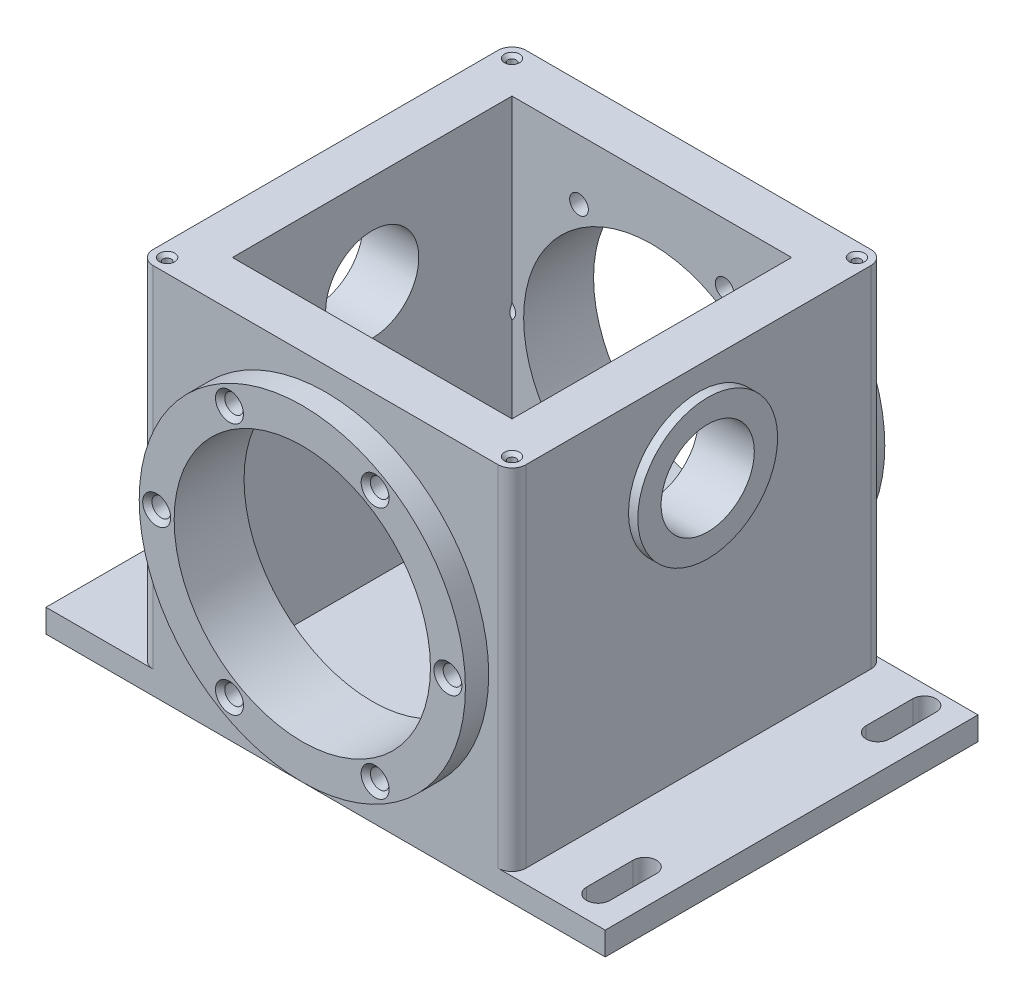
SolidWorks part; units mm, degrees
ref_plane "Front Plane" through (0, 0, 0) normal (0, 0, 1) x (1, 0, 0)
ref_plane "Top Plane" through (0, 0, 0) normal (0, 1, 0) x (1, 0, 0)
ref_plane "Right Plane" through (0, 0, 0) normal (1, 0, 0) x (0, 0, -1)
sketch "Sketch4" plane through (0, 0, 0) normal (0, 1, 0) x (1, 0, 0)
  line L1 (-76.2, -50.8) -> (76.2, -50.8)
  line L2 (-76.2, -50.8) -> (-76.2, 50.8)
  line L3 (-76.2, 50.8) -> (76.2, 50.8)
  line L4 (76.2, -50.8) -> (76.2, 50.8)
  line L5 (-76.2, -50.8) -> (76.2, 50.8) construction
  line L6 (-76.2, 50.8) -> (76.2, -50.8) construction
  point P0 (0, 0)
  dimension "D1" = 152.4
  dimension "D2" = 101.6
extrude "Boss-Extrude3" add sketch "Sketch4" along normal blind 6.35
sketch "Sketch5" plane through (0, 6.35, 0) normal (0, 1, 0) x (1, 0, 0)
  line L0 (76.2, 50.8) -> (-76.2, 50.8) construction
  line L1 (-50.8, -50.8) -> (50.8, -50.8)
  line L2 (-50.8, -50.8) -> (-50.8, 50.8)
  line L3 (-50.8, 50.8) -> (50.8, 50.8)
  line L4 (50.8, -50.8) -> (50.8, 50.8)
  line L5 (-50.8, -50.8) -> (50.8, 50.8) construction
  line L6 (-50.8, 50.8) -> (50.8, -50.8) construction
  point P0 (0, 0)
  dimension "D1" = 101.6
extrude "Boss-Extrude4" add sketch "Sketch5" along normal blind 95.25
sketch "Sketch6" plane through (0, 101.6, 0) normal (0, 1, 0) x (1, 0, 0)
  line L5 (50.8, 50.8) -> (-50.8, 50.8) construction
  line L6 (-38.1, -38.1) -> (38.1, -38.1)
  line L10 (-38.1, -38.1) -> (-38.1, 38.1)
  line L11 (-38.1, 38.1) -> (38.1, 38.1)
  line L12 (38.1, -38.1) -> (38.1, 38.1)
  line L13 (-38.1, -38.1) -> (38.1, 38.1) construction
  line L14 (-38.1, 38.1) -> (38.1, -38.1) construction
  line L15 (50.8, -50.8) -> (50.8, 50.8) construction
  point P0 (0, 0)
  dimension "D1" = 12.7
  dimension "D2" = 12.7
extrude "Cut-Extrude1" cut sketch "Sketch6" against normal blind 95.25
sketch "Sketch7" plane through (0, 0, 50.8) normal (0, 0, 1) x (1, 0, 0)
  line L0 (-50.8, 101.6) -> (50.8, 101.6) construction
  circle A0 centre (0, 50.8) radius 44.45
  dimension "D1" = 88.9
  dimension "D2" = 50.8
extrude "Boss-Extrude5" add sketch "Sketch7" along normal blind 6.35
mirror "Mirror2" about plane through (0, 0, 0) normal (0, 0, 1) of "Boss-Extrude5"
sketch "Sketch8" plane through (0, 0, 57.15) normal (0, 0, 1) x (1, 0, 0)
  circle A0 centre (0, 50.8) radius 34.925
  circle A1 centre (0, 50.8) radius 44.45 construction
  dimension "D1" = 69.85
extrude "Cut-Extrude3" cut sketch "Sketch8" against normal through all
hole_wizard "1/4-20 Tapped Hole2" positions "Sketch12" profile "Sketch13" tap size "1/4-20" standard "ANSI Inch"
sketch "Sketch12" plane through (0, 0, 57.15) normal (0, 0, 1) x (1, 0, 0)
  line L0 (34.925, 50.8) -> (44.45, 50.8) construction
  circle A0 centre (0, 50.8) radius 34.925 construction
  circle A1 centre (0, 50.8) radius 44.45 construction
  point P10 (39.6875, 50.8)
sketch "Sketch13" plane through (39.6875, 50.8, 57.15) normal (1, 0, 0) x (0, -1, 0)
  line L0 (0, 0) -> (0, 20.5838)
  line L1 (0, 20.5838) -> (2.5527, 19.05)
  line L2 (2.5527, 19.05) -> (2.5527, 1.2573)
  line L3 (2.5527, 1.2573) -> (3.81, 0)
  line L5 (3.81, 0) -> (0, 0)
  line L6 (-2.5527, 1.2573) -> (-3.81, 0) construction
  line L10 (0, 20.5838) -> (-2.5527, 19.05) construction
  line L11 (0, -6.35) -> (0, 107.95) construction
  dimension "Tap Drill Dia." = 5.1054
  dimension "Tap Drill Depth" = 19.05
  dimension "Near C'Sink Dia." = 7.62
  dimension "Near C'Sink Angle" = 90
  dimension "Drill Angle" = 118
cosmetic thread "Hole Thread2" parameters "D1"=12.7, "D2"=6.35
pattern_circular "CirPattern1" count 6 over 360 about axis through (0, 50.8, 0) along (0, 0, 1) of "1/4-20 Tapped Hole2"
cosmetic thread "Hole Thread23" parameters "D1"=12.7, "D2"=6.35
cosmetic thread "Hole Thread24" parameters "D1"=12.7, "D2"=6.35
cosmetic thread "Hole Thread25" parameters "D1"=12.7, "D2"=6.35
cosmetic thread "Hole Thread26" parameters "D1"=12.7, "D2"=6.35
cosmetic thread "Hole Thread27" parameters "D1"=12.7, "D2"=6.35
fillet "Fillet1" radius 3.81 4 edges at (-50.8, 53.975, 50.8) (-50.8, 53.975, -50.8) (50.8, 53.975, -50.8) (50.8, 53.975, 50.8)
hole_wizard "#4-40 Tapped Hole1" positions "Sketch14" profile "Sketch15" tap size "#4-40" standard "ANSI Inch"
sketch "Sketch14" plane through (0, 101.6, 0) normal (0, 1, 0) x (1, 0, 0)
  point P0 (-46.99, 46.99)
  point P4 (46.99, 46.99)
  point P7 (46.99, -46.99)
  point P10 (-46.99, -46.99)
sketch "Sketch15" plane through (-46.99, 101.6, -46.99) normal (1, 0, 0) x (0, 0, 1)
  line L0 (0, 0) -> (0, 9.5438)
  line L1 (0, 9.5438) -> (1.1303, 8.8646)
  line L2 (1.1303, 8.8646) -> (1.1303, 0.9271)
  line L3 (1.1303, 0.9271) -> (2.0574, 0)
  line L5 (2.0574, 0) -> (0, 0)
  line L6 (-1.1303, 0.9271) -> (-2.0574, 0) construction
  line L10 (0, 9.5438) -> (-1.1303, 8.8646) construction
  line L11 (0, -6.35) -> (0, 107.95) construction
  dimension "Tap Drill Dia." = 2.2606
  dimension "Tap Drill Depth" = 8.8646
  dimension "Near C'Sink Dia." = 4.1148
  dimension "Near C'Sink Angle" = 90
  dimension "Drill Angle" = 118
cosmetic thread "Hole Thread19" parameters "D1"=5.6896, "D2"=2.8448
cosmetic thread "Hole Thread20" parameters "D1"=5.6896, "D2"=2.8448
cosmetic thread "Hole Thread21" parameters "D1"=5.6896, "D2"=2.8448
cosmetic thread "Hole Thread22" parameters "D1"=5.6896, "D2"=2.8448
sketch "Sketch16" plane through (50.8, 0, 0) normal (1, 0, 0) x (0, 0, -1)
  line L0 (-46.99, 101.6) -> (46.99, 101.6) construction
  circle A0 centre (0, 76.2) radius 19.05
  point P2 (0, 0)
  point P4 (0, 0)
  dimension "D1" = 38.1
  dimension "D2" = 25.4
extrude "Boss-Extrude6" add sketch "Sketch16" along normal blind 2.54
mirror "Mirror4" about plane through (0, 0, 0) normal (1, 0, 0) of "Boss-Extrude6"
sketch "Sketch17" plane through (53.34, 0, 0) normal (1, 0, 0) x (0, 0, -1)
  circle A0 centre (0, 76.2) radius 12.7
  circle A1 centre (0, 76.2) radius 19.05 construction
  dimension "D1" = 25.4
extrude "Cut-Extrude4" cut sketch "Sketch17" against normal through all and the other way through all
mirror "Mirror5" about plane through (0, 0, 0) normal (0, 0, 1) of "CirPattern1", "1/4-20 Tapped Hole2"
cosmetic thread "Hole Thread28" parameters "D1"=12.7, "D2"=6.35
cosmetic thread "Hole Thread29" parameters "D1"=12.7, "D2"=6.35
cosmetic thread "Hole Thread30" parameters "D1"=12.7, "D2"=6.35
cosmetic thread "Hole Thread31" parameters "D1"=12.7, "D2"=6.35
cosmetic thread "Hole Thread32" parameters "D1"=12.7, "D2"=6.35
cosmetic thread "Hole Thread33" parameters "D1"=12.7, "D2"=6.35
sketch "Sketch19" plane through (0, 6.35, 0) normal (0, 1, 0) x (1, 0, 0)
  line L0 (66.675, -30.48) -> (66.675, -43.18) construction
  line L1 (69.85, -30.48) -> (69.85, -43.18)
  line L2 (63.5, -30.48) -> (63.5, -43.18)
  line L3 (76.2, -50.8) -> (76.2, 50.8) construction
  line L4 (46.99, -50.8) -> (76.2, -50.8) construction
  arc A0 (69.85, -30.48) -> (63.5, -30.48) centre (66.675, -30.48) ccw
  arc A1 (63.5, -43.18) -> (69.85, -43.18) centre (66.675, -43.18) ccw
  point P2 (66.675, -36.83)
  dimension "D1" = 6.35
  dimension "D2" = 12.7
  dimension "D3" = 6.35
  dimension "D4" = 7.62
extrude "Cut-Extrude5" cut sketch "Sketch19" against normal through all
pattern_linear "LPattern1" count 2 spacing 76.2 along (0, 0, -1) of "Cut-Extrude5"
